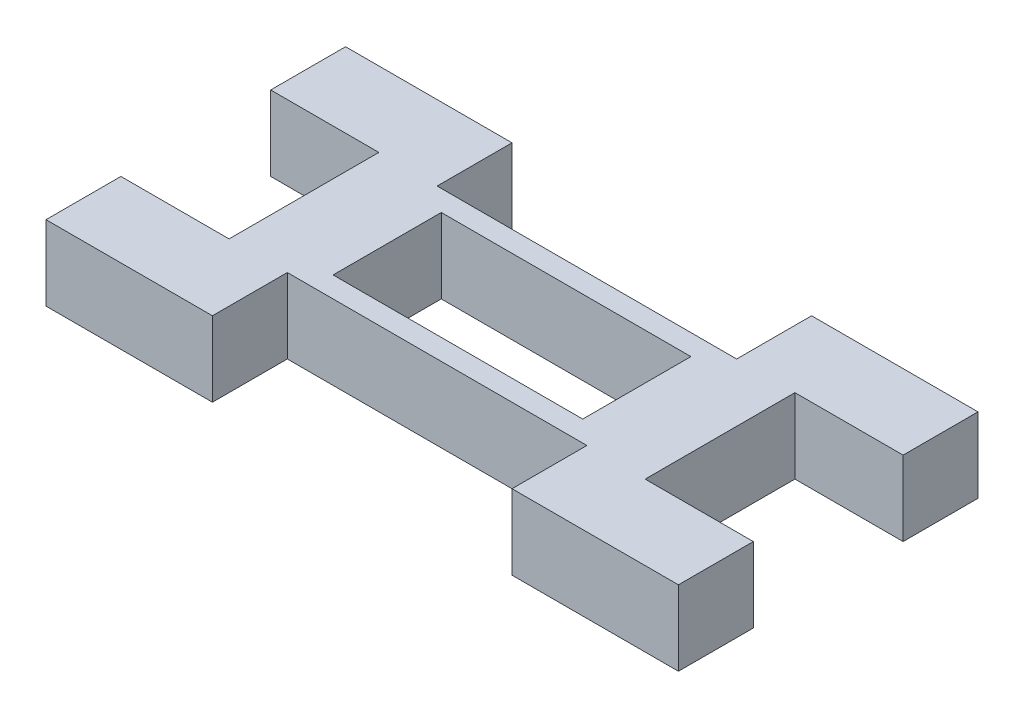
SolidWorks part; units mm, degrees
ref_plane "Front Plane" through (0, 0, 0) normal (0, 0, 1) x (1, 0, 0)
ref_plane "Top Plane" through (0, 0, 0) normal (0, 1, 0) x (1, 0, 0)
ref_plane "Right Plane" through (0, 0, 0) normal (1, 0, 0) x (0, 0, -1)
sketch "Sketch1" plane through (0, 0, 0) normal (0, 1, 0) x (1, 0, 0)
  line L1 (-27.5, -4.5) -> (27.5, -4.5)
  line L2 (-27.5, -4.5) -> (-27.5, 4.5)
  line L3 (-27.5, 4.5) -> (27.5, 4.5)
  line L4 (27.5, -4.5) -> (27.5, 4.5)
  line L5 (-27.5, -4.5) -> (27.5, 4.5) construction
  line L6 (-27.5, 4.5) -> (27.5, -4.5) construction
  point P0 (0, 0)
  dimension "D1" = 55
  dimension "D2" = 9
extrude "Boss-Extrude1" add sketch "Sketch1" along normal blind 4.5
sketch "Sketch2" plane through (0, 4.5, 0) normal (0, 1, 0) x (1, 0, 0)
  line L0 (-27.5, 0) -> (27.5, 0) construction
  line L1 (-27.5, 4.5) -> (-27.5, -4.5) construction
  line L2 (27.5, -4.5) -> (27.5, 4.5) construction
  line L3 (0, 4.5) -> (0, -4.5) construction
  line L4 (27.5, 4.5) -> (-27.5, 4.5) construction
  line L5 (-27.5, -4.5) -> (27.5, -4.5) construction
  line L6 (-27.5, -4.5) -> (-27.5, -9) construction
  line L7 (-27.5, -9) -> (27.5, -9) construction
  line L8 (0, -9) -> (0, -4.5) construction
  line L9 (-19, -4.5) -> (-19, -9)
  line L10 (-19, -9) -> (-9, -9)
  line L11 (-9, -9) -> (-9, -4.5)
  line L12 (-9, -4.5) -> (-19, -4.5)
  line L13 (-14, -9) -> (-14, -4.5) construction
  line L14 (14, -9) -> (14, -4.5) construction
  line L15 (27.5, -4.5) -> (27.5, -9) construction
  line L16 (9, -4.5) -> (19, -4.5)
  line L17 (9, -9) -> (9, -4.5)
  line L18 (19, -9) -> (9, -9)
  line L19 (19, -4.5) -> (19, -9)
  line L20 (27.5, 4.5) -> (27.5, 9) construction
  line L21 (14, 9) -> (14, 4.5) construction
  line L22 (-14, 9) -> (-14, 4.5) construction
  line L23 (0, 9) -> (0, 4.5) construction
  line L24 (-27.5, 9) -> (27.5, 9) construction
  line L25 (-27.5, 4.5) -> (-27.5, 9) construction
  line L26 (19, 4.5) -> (19, 9)
  line L27 (19, 9) -> (9, 9)
  line L28 (9, 9) -> (9, 4.5)
  line L29 (9, 4.5) -> (19, 4.5)
  line L30 (-9, 4.5) -> (-19, 4.5)
  line L31 (-9, 9) -> (-9, 4.5)
  line L32 (-19, 9) -> (-9, 9)
  line L33 (-19, 4.5) -> (-19, 9)
  dimension "D1" = 4.5
  dimension "D2" = 10
  dimension "D3" = 14
extrude "Boss-Extrude2" add sketch "Sketch2" against normal through all
sketch "Sketch3" plane through (0, 4.5, 0) normal (0, 1, 0) x (1, 0, 0)
  line L0 (-27.5, 0) -> (27.5, 0) construction
  line L1 (-27.5, 4.5) -> (-27.5, -4.5) construction
  line L2 (27.5, -4.5) -> (27.5, 4.5) construction
  line L3 (0, -4.5) -> (0, 4.5) construction
  line L4 (-42.5, 4.5) -> (-12.5, 4.5)
  line L5 (-42.5, 4.5) -> (-42.5, -4.5)
  line L6 (-42.5, -4.5) -> (-12.5, -4.5)
  line L7 (-12.5, 4.5) -> (-12.5, -4.5)
  line L8 (-42.5, 4.5) -> (-12.5, -4.5) construction
  line L9 (-42.5, -4.5) -> (-12.5, 4.5) construction
  line L10 (-9, -4.5) -> (9, -4.5) construction
  line L11 (9, 4.5) -> (-9, 4.5) construction
  line L12 (42.5, -4.5) -> (12.5, 4.5) construction
  line L13 (42.5, 4.5) -> (12.5, -4.5) construction
  line L14 (12.5, 4.5) -> (12.5, -4.5)
  line L15 (42.5, -4.5) -> (12.5, -4.5)
  line L16 (42.5, 4.5) -> (42.5, -4.5)
  line L17 (42.5, 4.5) -> (12.5, 4.5)
  line L18 (-42.5, -4.5) -> (-12.5, 4.5) construction
  line L20 (-7.5, -3.25) -> (7.5, -3.25)
  line L21 (-7.5, -3.25) -> (-7.5, 3.25)
  line L22 (-7.5, 3.25) -> (7.5, 3.25)
  line L23 (7.5, -3.25) -> (7.5, 3.25)
  line L24 (-7.5, -3.25) -> (7.5, 3.25) construction
  line L25 (-7.5, 3.25) -> (7.5, -3.25) construction
  point P20 (0, 0)
  dimension "D1" = 9
  dimension "D2" = 15
  dimension "D3" = 6.5
  dimension "D4" = 5
extrude "Cut-Extrude1" cut sketch "Sketch3" against normal through all and the other way through all
equation "\"X-ROD-SPACING\"=45"
equation "\"Y-ROD-SPACING\"=75"
equation "\"Z-ROD-SPACING\"=17.5"
equation "\"Y-BED-OFFSET\"=2"
equation "\"Y-BED-ROD-INSET\"=3.5"
equation "\"Y-BED-SCREW-SPACING\"=209"
equation "\"Y-BED-SCREW-CUTOUT-SLOT-HEIGHT\"=1"
equation "\"T-SLOT-NUT-FILLET-RADIUS\"=0.25"
equation "\"T-SLOT-SCREW-SHAFT-RADIUS\"=1.75"
equation "\"T-SLOT-SCREW-SHAFT-CUTOUT-LENGTH\"=10.5"
equation "\"T-SLOT-NUT-DEPTH\"=4.2"
equation "\"T-SLOT-NUT-WIDTH\"=3"
equation "\"T-SLOT-NUT-END-DISTANCE\"=8"
equation "\"ACRYLIC-THICKNESS\"=10"
equation "\"ACRYLIC-THICKNESS2\"=4.5"
equation "\"ACRYLIC-TAB-CUTOUT-SIZE\"=\"ACRYLIC-THICKNESS\"+\"ACRYLIC-TAB-TOLERANCE\"*2"
equation "\"ACRYLIC-TAB-WIDTH\"=\"ACRYLIC-THICKNESS\""
equation "\"ACRYLIC-M3-HOLE\"=3.2"
equation "\"SMOOTHROD-CAP-SCREW-DISTANCE\"=20"
equation "\"FRAME-WIDTH-INNER\"=370"
equation "\"NEMA17-HOLE-SPACING\"=31"
equation "\"NEMA17-CENTRAL-CUTOUT\"=22.5"
equation "\"Z-BRACKET-REACH\"=55"
equation "\"Z-ROD-INSET\"=16"
equation "\"TOP-BRACKET-SPACING\"=40"
equation "\"SMOOTHROD-X-LENGTH\"=350"
equation "\"SMOOTHROD-Y-LENGTH\"=350"
equation "\"SMOOTHROD-Z-LENGTH\"=350"
equation "\"SMOOTHROD-TIGHTENING-HEADROOM\"=1"
equation "\"LEADSCREW-Z-LENGTH\"=300"
equation "\"SCREW-LENGTH-FRAME\"=\"ACRYLIC-THICKNESS\" + 10"
equation "\"SCREW-LENGTH-MOTOR\"=\"ACRYLIC-THICKNESS\" + 5"
equation "\"SCREW-HEAD-RADIUS\"=6"
equation "\"PRINTED-X-SMOOTHROD-DIAMETER\"=8.2"
equation "\"PRINTED-X-SMOOTHROD-CUTOUT\"=10"
equation "\"PRINTED-X-BASE-HEIGHT\"=10"
equation "\"PRINTED-LM8UU-CUTOUT-SIZE\"=16"
equation "\"PRINTED-LM8UU-CUTOUT-LENGTH\"=24.5"
equation "\"PRINTED-X-IDLER-HEIGHT\"=16"
equation "\"PSU-MOUNTING-WIDTH\"=95"
equation "\"PSU-MOUNTING-HEIGHT\"=177"
equation "\"Y-BELT-TO-ROD-DISTANCE\"=20"
equation "\"SPOOL-HOLDER-ROD-SPACING\"=150"
equation "\"ACRYLIC-X-CARRIAGE-WIDTH\"=55"
equation "\"ACRYLIC-X-CARRIAGE-HEIGHT\"=75"
equation "\"D1@Sketch1\"=\"ACRYLIC-X-CARRIAGE-WIDTH\""
equation "\"D1@Boss-Extrude1\"=\"ACRYLIC-THICKNESS2\""
equation "\"D1@Sketch2\"=\"ACRYLIC-THICKNESS2\""
equation "\"D2@Sketch2\"=\"ACRYLIC-TAB-WIDTH\""
equation "\"ACRYLIC-X-CARRIAGE-CENTER-TAB-SPACING\"=14"
equation "\"D3@Sketch2\"=\"ACRYLIC-X-CARRIAGE-CENTER-TAB-SPACING\""
